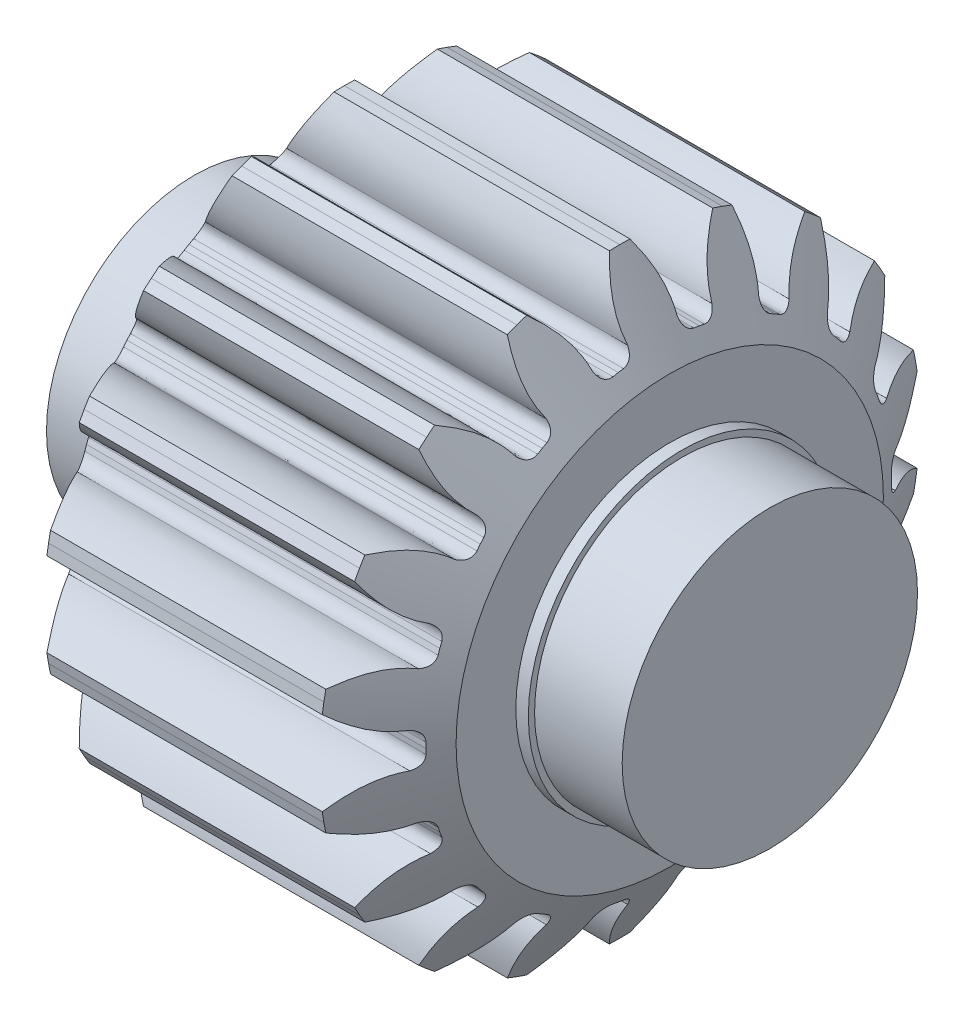
SolidWorks part; units mm, degrees
ref_plane "Front Plane" through (0, 0, 0) normal (0, 0, 1) x (1, 0, 0)
ref_plane "Top Plane" through (0, 0, 0) normal (0, 1, 0) x (1, 0, 0)
ref_plane "Right Plane" through (0, 0, 0) normal (1, 0, 0) x (0, 0, -1)
other "Graphic1"
sketch "Sketch3" plane through (0, 0, 0) normal (0, 0, 1) x (1, 0, 0)
  line L0 (98.5, 42.3588) -> (102, 42.3588)
  line L1 (102, 42.3588) -> (102, 42.6088)
  line L2 (102, 42.6088) -> (102.5, 42.6088)
  line L3 (102.5, 42.6088) -> (102.5, 44.9947)
  line L4 (102.5, 44.9947) -> (104.5, 48.4588)
  line L5 (104.5, 48.4588) -> (115.5, 48.4588)
  line L6 (110, 58.4318) -> (110, 23.1509) construction
  line L7 (121.5, 42.3588) -> (121.5, 36.4588)
  line L8 (121.5, 42.3588) -> (118, 42.3588)
  line L9 (118, 42.3588) -> (118, 42.6088)
  line L10 (118, 42.6088) -> (117.5, 42.6088)
  line L11 (117.5, 42.6088) -> (117.5, 44.9947)
  line L12 (117.5, 44.9947) -> (115.5, 48.4588)
  line L13 (98.5, 42.3588) -> (98.5, 36.4588)
  line L14 (98.5, 36.4588) -> (121.5, 36.4588)
  line L15 (104.5, 24.4588) -> (115.5, 24.4588) construction
  line L16 (78.4379, 36.4588) -> (152.6177, 36.4588) construction
  point P20 (110, 48.4588)
  dimension "D1" = 0.5
  dimension "D2" = 0.25
  dimension "D3" = 5.5
  dimension "D4" = 3.5
  dimension "D5" = 24
  dimension "D6" = 12
  dimension "D7" = 5.9
  dimension "D8" = 2
  dimension "D9" = 4
revolve "Revolve1" add sketch "Sketch3" angle 360 about L16
sketch "Sketch4" plane through (121.5, 0, 0) normal (1, 0, 0) x (0, 0, -1)
  line L0 (0, 36.4588) -> (0, 54.7636) construction
  line L1 (0, 36.4588) -> (25.1437, 36.4588) construction
  line L2 (0, 36.4588) -> (6.2436, 53.6131) construction
  line L3 (0, 48.4588) -> (0.4119, 48.4518)
  line L4 (0, 36.4588) -> (3.637, 57.085) construction
  line L5 (1.6156, 45.6212) -> (1.4042, 45.6522)
  line L6 (1.6156, 45.6212) -> (1.8248, 45.578)
  line L7 (4.1042, 47.7351) -> (3.7148, 47.8694)
  line L8 (4.1042, 47.7351) -> (4.4889, 47.5876)
  line L9 (4.6519, 44.5161) -> (4.4638, 44.6175)
  line L10 (4.6519, 44.5161) -> (4.8337, 44.4039)
  line L11 (7.7135, 45.6514) -> (7.3934, 45.9107)
  line L12 (7.7135, 45.6514) -> (8.0244, 45.3812)
  line L13 (7.1271, 42.4392) -> (6.985, 42.5988)
  line L14 (7.1271, 42.4392) -> (7.2596, 42.2716)
  line L15 (10.3923, 42.4588) -> (10.1802, 42.812)
  line L16 (10.3923, 42.4588) -> (10.5921, 42.0986)
  line L17 (8.7426, 39.6409) -> (8.6638, 39.8394)
  line L18 (8.7426, 39.6409) -> (8.8098, 39.4381)
  line L19 (11.8177, 38.5426) -> (11.7392, 38.947)
  line L20 (11.8177, 38.5426) -> (11.8823, 38.1357)
  line L21 (9.3037, 36.4588) -> (9.2975, 36.6724)
  line L22 (9.3037, 36.4588) -> (9.2975, 36.2453)
  line L23 (11.8177, 34.3751) -> (11.8823, 34.7819)
  line L24 (11.8177, 34.3751) -> (11.7392, 33.9706)
  line L25 (8.7426, 33.2768) -> (8.8098, 33.4796)
  line L26 (8.7426, 33.2768) -> (8.6638, 33.0782)
  line L27 (10.3923, 30.4588) -> (10.5921, 30.8191)
  line L28 (10.3923, 30.4588) -> (10.1802, 30.1057)
  line L29 (7.1271, 30.4785) -> (7.2596, 30.6461)
  line L30 (7.1271, 30.4785) -> (6.985, 30.3189)
  line L31 (7.7135, 27.2663) -> (8.0244, 27.5365)
  line L32 (7.7135, 27.2663) -> (7.3934, 27.007)
  line L33 (4.6519, 28.4016) -> (4.8337, 28.5137)
  line L34 (4.6519, 28.4016) -> (4.4638, 28.3002)
  line L35 (4.1042, 25.1825) -> (4.4889, 25.33)
  line L36 (4.1042, 25.1825) -> (3.7148, 25.0483)
  line L37 (1.6156, 27.2965) -> (1.8248, 27.3397)
  line L38 (1.6156, 27.2965) -> (1.4042, 27.2655)
  line L39 (0, 24.4588) -> (0.4119, 24.4659)
  line L40 (0, 24.4588) -> (-0.4119, 24.4659)
  line L41 (-1.6156, 27.2965) -> (-1.4042, 27.2655)
  line L42 (-1.6156, 27.2965) -> (-1.8248, 27.3397)
  line L43 (-4.1042, 25.1825) -> (-3.7148, 25.0483)
  line L44 (-4.1042, 25.1825) -> (-4.4889, 25.33)
  line L45 (-4.6519, 28.4016) -> (-4.4638, 28.3002)
  line L46 (-4.6519, 28.4016) -> (-4.8337, 28.5137)
  line L47 (-7.7135, 27.2663) -> (-7.3934, 27.007)
  line L48 (-7.7135, 27.2663) -> (-8.0244, 27.5365)
  line L49 (-7.1271, 30.4785) -> (-6.985, 30.3189)
  line L50 (-7.1271, 30.4785) -> (-7.2596, 30.6461)
  line L51 (-10.3923, 30.4588) -> (-10.1802, 30.1057)
  line L52 (-10.3923, 30.4588) -> (-10.5921, 30.8191)
  line L53 (-8.7426, 33.2768) -> (-8.6638, 33.0782)
  line L54 (-8.7426, 33.2768) -> (-8.8098, 33.4796)
  line L55 (-11.8177, 34.3751) -> (-11.7392, 33.9706)
  line L56 (-11.8177, 34.3751) -> (-11.8823, 34.7819)
  line L57 (-9.3037, 36.4588) -> (-9.2975, 36.2453)
  line L58 (-9.3037, 36.4588) -> (-9.2975, 36.6724)
  line L59 (-11.8177, 38.5426) -> (-11.8823, 38.1357)
  line L60 (-11.8177, 38.5426) -> (-11.7392, 38.947)
  line L61 (-8.7426, 39.6409) -> (-8.8098, 39.4381)
  line L62 (-8.7426, 39.6409) -> (-8.6638, 39.8394)
  line L63 (-10.3923, 42.4588) -> (-10.5921, 42.0986)
  line L64 (-10.3923, 42.4588) -> (-10.1802, 42.812)
  line L65 (-7.1271, 42.4392) -> (-7.2596, 42.2716)
  line L66 (-7.1271, 42.4392) -> (-6.985, 42.5988)
  line L67 (-7.7135, 45.6514) -> (-8.0244, 45.3812)
  line L68 (-7.7135, 45.6514) -> (-7.3934, 45.9107)
  line L69 (-4.6519, 44.5161) -> (-4.8337, 44.4039)
  line L70 (-4.6519, 44.5161) -> (-4.4638, 44.6175)
  line L71 (-4.1042, 47.7351) -> (-4.4889, 47.5876)
  line L72 (-4.1042, 47.7351) -> (-3.7148, 47.8694)
  line L73 (-1.6156, 45.6212) -> (-1.8248, 45.578)
  line L74 (-1.6156, 45.6212) -> (-1.4042, 45.6522)
  line L75 (0, 48.4588) -> (-0.4119, 48.4518)
  circle A0 centre (0, 36.4588) radius 13.9777
  spline S0 degree 3 poles (0.4119, 48.4518) (0.8341, 47.7217) (1.1193, 46.9851) (0.9943, 46.1331) knots 0 0 0 0 1 1 1 1
  spline S1 degree 2 poles (0.9943, 46.1331) (1.0285, 45.7309) (1.4042, 45.6522) knots 0 0 0 1 1 1
  spline S2 degree 2 poles (2.3744, 45.8897) (2.2048, 45.5235) (1.8248, 45.578) knots 0 0 0 1 1 1
  spline S3 degree 3 poles (3.7148, 47.8694) (3.0684, 47.3277) (2.5483, 46.7331) (2.3744, 45.8897) knots 0 0 0 0 1 1 1 1
  spline S4 degree 3 poles (4.4889, 47.5876) (4.6359, 46.7572) (4.652, 45.9674) (4.2431, 45.2096) knots 0 0 0 0 1 1 1 1
  spline S5 degree 2 poles (4.2431, 45.2096) (4.1377, 44.82) (4.4638, 44.6175) knots 0 0 0 1 1 1
  spline S6 degree 2 poles (5.4568, 44.5089) (5.1721, 44.2228) (4.8337, 44.4039) knots 0 0 0 1 1 1
  spline S7 degree 3 poles (7.3934, 45.9107) (6.6007, 45.6228) (5.9087, 45.2419) (5.4568, 44.5089) knots 0 0 0 0 1 1 1 1
  spline S8 degree 3 poles (8.0244, 45.3812) (7.8785, 44.5505) (7.6236, 43.8029) (6.9802, 43.2306) knots 0 0 0 0 1 1 1 1
  spline S9 degree 2 poles (6.9802, 43.2306) (6.7479, 42.9006) (6.985, 42.5988) knots 0 0 0 1 1 1
  spline S10 degree 2 poles (7.881, 42.1571) (7.5156, 41.9856) (7.2596, 42.2716) knots 0 0 0 1 1 1
  spline S11 degree 3 poles (10.1802, 42.812) (9.3369, 42.8126) (8.5563, 42.6913) (7.881, 42.1571) knots 0 0 0 0 1 1 1 1
  spline S12 degree 3 poles (10.5921, 42.0986) (10.1709, 41.3679) (9.6756, 40.7526) (8.8753, 40.4348) knots 0 0 0 0 1 1 1 1
  spline S13 degree 2 poles (8.8753, 40.4348) (8.5441, 40.2042) (8.6638, 39.8394) knots 0 0 0 1 1 1
  spline S14 degree 2 poles (9.3546, 39.118) (8.9526, 39.0818) (8.8098, 39.4381) knots 0 0 0 1 1 1
  spline S15 degree 3 poles (11.7392, 38.947) (10.9469, 39.236) (10.1719, 39.389) (9.3546, 39.118) knots 0 0 0 0 1 1 1 1
  spline S16 degree 3 poles (11.8823, 38.1357) (11.2366, 37.5932) (10.5607, 37.1843) (9.6999, 37.1595) knots 0 0 0 0 1 1 1 1
  spline S17 degree 2 poles (9.6999, 37.1595) (9.3098, 37.0561) (9.2975, 36.6724) knots 0 0 0 1 1 1
  spline S18 degree 2 poles (9.6999, 35.7581) (9.3098, 35.8616) (9.2975, 36.2453) knots 0 0 0 1 1 1
  spline S19 degree 3 poles (11.8823, 34.7819) (11.2366, 35.3245) (10.5607, 35.7333) (9.6999, 35.7581) knots 0 0 0 0 1 1 1 1
  spline S20 degree 3 poles (11.7392, 33.9706) (10.9469, 33.6817) (10.1719, 33.5286) (9.3546, 33.7997) knots 0 0 0 0 1 1 1 1
  spline S21 degree 2 poles (9.3546, 33.7997) (8.9526, 33.8359) (8.8098, 33.4796) knots 0 0 0 1 1 1
  spline S22 degree 2 poles (8.8753, 32.4828) (8.5441, 32.7135) (8.6638, 33.0782) knots 0 0 0 1 1 1
  spline S23 degree 3 poles (10.5921, 30.8191) (10.1709, 31.5497) (9.6756, 32.1651) (8.8753, 32.4828) knots 0 0 0 0 1 1 1 1
  spline S24 degree 3 poles (10.1802, 30.1057) (9.3369, 30.1051) (8.5563, 30.2263) (7.881, 30.7606) knots 0 0 0 0 1 1 1 1
  spline S25 degree 2 poles (7.881, 30.7606) (7.5156, 30.9321) (7.2596, 30.6461) knots 0 0 0 1 1 1
  spline S26 degree 2 poles (6.9802, 29.6871) (6.7479, 30.0171) (6.985, 30.3189) knots 0 0 0 1 1 1
  spline S27 degree 3 poles (8.0244, 27.5365) (7.8785, 28.3671) (7.6236, 29.1148) (6.9802, 29.6871) knots 0 0 0 0 1 1 1 1
  spline S28 degree 3 poles (7.3934, 27.007) (6.6007, 27.2949) (5.9087, 27.6758) (5.4568, 28.4088) knots 0 0 0 0 1 1 1 1
  spline S29 degree 2 poles (5.4568, 28.4088) (5.1721, 28.6949) (4.8337, 28.5137) knots 0 0 0 1 1 1
  spline S30 degree 2 poles (4.2431, 27.7081) (4.1377, 28.0977) (4.4638, 28.3002) knots 0 0 0 1 1 1
  spline S31 degree 3 poles (4.4889, 25.33) (4.6359, 26.1605) (4.652, 26.9503) (4.2431, 27.7081) knots 0 0 0 0 1 1 1 1
  spline S32 degree 3 poles (3.7148, 25.0483) (3.0684, 25.59) (2.5483, 26.1846) (2.3744, 27.0279) knots 0 0 0 0 1 1 1 1
  spline S33 degree 2 poles (2.3744, 27.0279) (2.2048, 27.3941) (1.8248, 27.3397) knots 0 0 0 1 1 1
  spline S34 degree 2 poles (0.9943, 26.7846) (1.0285, 27.1867) (1.4042, 27.2655) knots 0 0 0 1 1 1
  spline S35 degree 3 poles (0.4119, 24.4659) (0.8341, 25.196) (1.1193, 25.9326) (0.9943, 26.7846) knots 0 0 0 0 1 1 1 1
  spline S36 degree 3 poles (-0.4119, 24.4659) (-0.8341, 25.196) (-1.1193, 25.9326) (-0.9943, 26.7846) knots 0 0 0 0 1 1 1 1
  spline S37 degree 2 poles (-0.9943, 26.7846) (-1.0285, 27.1867) (-1.4042, 27.2655) knots 0 0 0 1 1 1
  spline S38 degree 2 poles (-2.3744, 27.0279) (-2.2048, 27.3941) (-1.8248, 27.3397) knots 0 0 0 1 1 1
  spline S39 degree 3 poles (-3.7148, 25.0483) (-3.0684, 25.59) (-2.5483, 26.1846) (-2.3744, 27.0279) knots 0 0 0 0 1 1 1 1
  spline S40 degree 3 poles (-4.4889, 25.33) (-4.6359, 26.1605) (-4.652, 26.9503) (-4.2431, 27.7081) knots 0 0 0 0 1 1 1 1
  spline S41 degree 2 poles (-4.2431, 27.7081) (-4.1377, 28.0977) (-4.4638, 28.3002) knots 0 0 0 1 1 1
  spline S42 degree 2 poles (-5.4568, 28.4088) (-5.1721, 28.6949) (-4.8337, 28.5137) knots 0 0 0 1 1 1
  spline S43 degree 3 poles (-7.3934, 27.007) (-6.6007, 27.2949) (-5.9087, 27.6758) (-5.4568, 28.4088) knots 0 0 0 0 1 1 1 1
  spline S44 degree 3 poles (-8.0244, 27.5365) (-7.8785, 28.3671) (-7.6236, 29.1148) (-6.9802, 29.6871) knots 0 0 0 0 1 1 1 1
  spline S45 degree 2 poles (-6.9802, 29.6871) (-6.7479, 30.0171) (-6.985, 30.3189) knots 0 0 0 1 1 1
  spline S46 degree 2 poles (-7.881, 30.7606) (-7.5156, 30.9321) (-7.2596, 30.6461) knots 0 0 0 1 1 1
  spline S47 degree 3 poles (-10.1802, 30.1057) (-9.3369, 30.1051) (-8.5563, 30.2263) (-7.881, 30.7606) knots 0 0 0 0 1 1 1 1
  spline S48 degree 3 poles (-10.5921, 30.8191) (-10.1709, 31.5497) (-9.6756, 32.1651) (-8.8753, 32.4828) knots 0 0 0 0 1 1 1 1
  spline S49 degree 2 poles (-8.8753, 32.4828) (-8.5441, 32.7135) (-8.6638, 33.0782) knots 0 0 0 1 1 1
  spline S50 degree 2 poles (-9.3546, 33.7997) (-8.9526, 33.8359) (-8.8098, 33.4796) knots 0 0 0 1 1 1
  spline S51 degree 3 poles (-11.7392, 33.9706) (-10.9469, 33.6817) (-10.1719, 33.5286) (-9.3546, 33.7997) knots 0 0 0 0 1 1 1 1
  spline S52 degree 3 poles (-11.8823, 34.7819) (-11.2366, 35.3245) (-10.5607, 35.7333) (-9.6999, 35.7581) knots 0 0 0 0 1 1 1 1
  spline S53 degree 2 poles (-9.6999, 35.7581) (-9.3098, 35.8616) (-9.2975, 36.2453) knots 0 0 0 1 1 1
  spline S54 degree 2 poles (-9.6999, 37.1595) (-9.3098, 37.0561) (-9.2975, 36.6724) knots 0 0 0 1 1 1
  spline S55 degree 3 poles (-11.8823, 38.1357) (-11.2366, 37.5932) (-10.5607, 37.1843) (-9.6999, 37.1595) knots 0 0 0 0 1 1 1 1
  spline S56 degree 3 poles (-11.7392, 38.947) (-10.9469, 39.236) (-10.1719, 39.389) (-9.3546, 39.118) knots 0 0 0 0 1 1 1 1
  spline S57 degree 2 poles (-9.3546, 39.118) (-8.9526, 39.0818) (-8.8098, 39.4381) knots 0 0 0 1 1 1
  spline S58 degree 2 poles (-8.8753, 40.4348) (-8.5441, 40.2042) (-8.6638, 39.8394) knots 0 0 0 1 1 1
  spline S59 degree 3 poles (-10.5921, 42.0986) (-10.1709, 41.3679) (-9.6756, 40.7526) (-8.8753, 40.4348) knots 0 0 0 0 1 1 1 1
  spline S60 degree 3 poles (-10.1802, 42.812) (-9.3369, 42.8126) (-8.5563, 42.6913) (-7.881, 42.1571) knots 0 0 0 0 1 1 1 1
  spline S61 degree 2 poles (-7.881, 42.1571) (-7.5156, 41.9856) (-7.2596, 42.2716) knots 0 0 0 1 1 1
  spline S62 degree 2 poles (-6.9802, 43.2306) (-6.7479, 42.9006) (-6.985, 42.5988) knots 0 0 0 1 1 1
  spline S63 degree 3 poles (-8.0244, 45.3812) (-7.8785, 44.5505) (-7.6236, 43.8029) (-6.9802, 43.2306) knots 0 0 0 0 1 1 1 1
  spline S64 degree 3 poles (-7.3934, 45.9107) (-6.6007, 45.6228) (-5.9087, 45.2419) (-5.4568, 44.5089) knots 0 0 0 0 1 1 1 1
  spline S65 degree 2 poles (-5.4568, 44.5089) (-5.1721, 44.2228) (-4.8337, 44.4039) knots 0 0 0 1 1 1
  spline S66 degree 2 poles (-4.2431, 45.2096) (-4.1377, 44.82) (-4.4638, 44.6175) knots 0 0 0 1 1 1
  spline S67 degree 3 poles (-4.4889, 47.5876) (-4.6359, 46.7572) (-4.652, 45.9674) (-4.2431, 45.2096) knots 0 0 0 0 1 1 1 1
  spline S68 degree 3 poles (-3.7148, 47.8694) (-3.0684, 47.3277) (-2.5483, 46.7331) (-2.3744, 45.8897) knots 0 0 0 0 1 1 1 1
  spline S69 degree 2 poles (-2.3744, 45.8897) (-2.2048, 45.5235) (-1.8248, 45.578) knots 0 0 0 1 1 1
  spline S70 degree 2 poles (-0.9943, 46.1331) (-1.0285, 45.7309) (-1.4042, 45.6522) knots 0 0 0 1 1 1
  spline S71 degree 3 poles (-0.4119, 48.4518) (-0.8341, 47.7217) (-1.1193, 46.9851) (-0.9943, 46.1331) knots 0 0 0 0 1 1 1 1
  point P244 (0, 36.4588)
  dimension "D1" = 20
  dimension "D2" = 10
  dimension "D3" = 18
extrude "Cut-Extrude1" cut sketch "Sketch4" against normal through all
